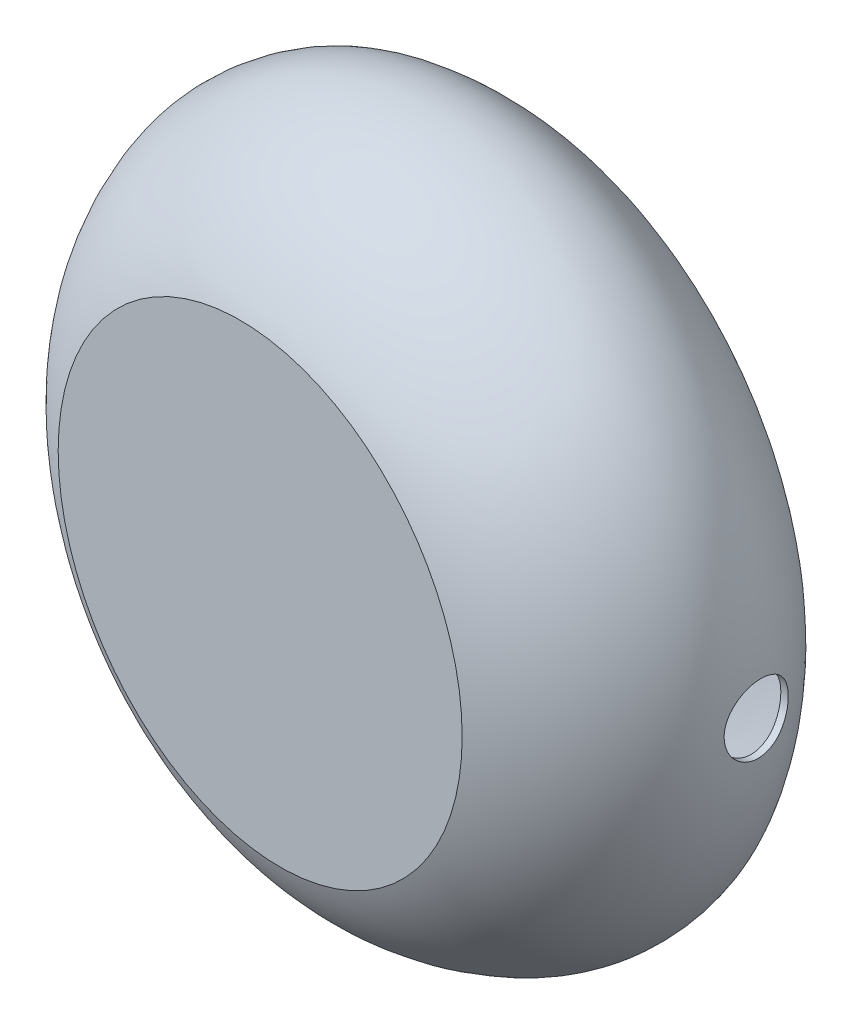
SolidWorks part; units mm, degrees
ref_plane "Front Plane" through (0, 0, 0) normal (0, 0, 1) x (1, 0, 0)
ref_plane "Top Plane" through (0, 0, 0) normal (0, 1, 0) x (1, 0, 0)
ref_plane "Right Plane" through (0, 0, 0) normal (1, 0, 0) x (0, 0, -1)
sketch "Sketch1" plane through (0, 0, 0) normal (0, 1, 0) x (1, 0, 0)
  line B0 (-17.3903, 2.1246) -> (14.7663, -1.1117)
  line B1 (-17.4904, 1.1296) -> (14.8664, -2.1268)
  spline B2 degree 3 poles (10.9564, 41.4839) (16.7468, 39.8909) (24.4853, 37.3647) (29.4108, 31.1888) (30.2373, 30.0002) (31.4004, 28.3276) (33.4007, 24.7556) (33.4337, 17.1975) (31.7954, 13.4401) (30.7823, 11.6726) (27.219, 5.4555) (21.6185, 0.9851) (14.7663, -1.1117) knots 0 0 0 0 0.295285 0.36618 0.36618 0.36618 0.465949 0.565717 0.665486 0.665486 0.665486 1 1 1 1 weights 1 1 1 1 1 1 1 1 1 1 0.953256 0.953256 1
  spline B3 degree 3 poles (14.8664, -2.1268) (15.5013, -1.9325) (16.7557, -1.5171) (19.2527, -0.4775) (22.2561, 1.1586) (25.5709, 3.6387) (28.4903, 6.5544) (30.9261, 9.8228) (32.8726, 13.2761) (34.198, 17.3119) (34.4104, 21.2826) (34.0019, 24.3442) (33.1591, 27.1572) (31.8171, 29.5229) (30.2806, 31.6773) (28.9643, 33.2881) (27.4967, 34.7819) (24.3248, 37.4218) (20.0627, 39.6118) (15.6203, 41.1621) (13.0865, 41.9278) (11.8468, 42.2761) (11.2217, 42.4481) knots 0 0 0 0 0.031353 0.062705 0.125411 0.188116 0.250821 0.313527 0.376232 0.438937 0.501643 0.532995 0.564348 0.627054 0.658406 0.689759 0.721112 0.752464 0.877875 0.94058 0.971933 1.003286 1.003286 1.003286 1.003286
  line B4 (-17.3903, 2.1246) -> (-17.4904, 1.1296)
  line B5 (11.2217, 42.4481) -> (10.9564, 41.4839)
sketch_block_instance "googleHomeActualsize-1"
sketch_block "googleHomeActualsize"
revolve "Revolve1" add sketch "Sketch1" angle 360 about L2
sketch "Sketch2" plane through (0, 0, 0) normal (1, 0, 0) x (0, 0, -1)
  line L0 (0, 0) -> (43, 0) construction
  line L1 (0, 0) -> (21.5, 0)
  circle A0 centre (21.5, 0) radius 4.8727
  dimension "D1" = 43
  dimension "D2" = 21.5
extrude "Cut-Extrude1" cut sketch "Sketch2" against normal blind 70 and the other way blind 50 contours L0 L1 A0 | L1 L0 A0
